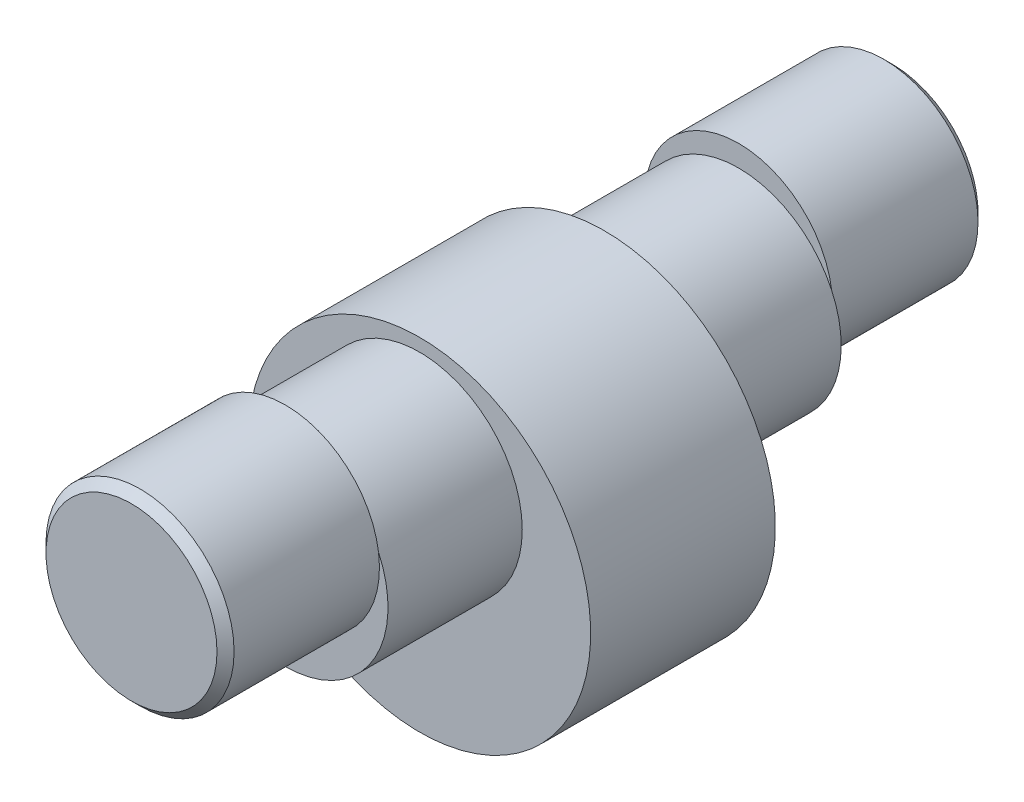
SolidWorks part; units mm, degrees
ref_plane "Plan de face" through (0, 0, 0) normal (0, 0, 1) x (1, 0, 0)
ref_plane "Plan de dessus" through (0, 0, 0) normal (0, 1, 0) x (1, 0, 0)
ref_plane "Plan de droite" through (0, 0, 0) normal (1, 0, 0) x (0, 0, -1)
sketch "Esquisse1" plane through (0, 0, 0) normal (0, 0, 1) x (1, 0, 0)
  circle A0 centre (0, 0) radius 20
  dimension "D1" = 40
extrude "Extrusion1" add sketch "Esquisse1" along normal mid plane 21.6
sketch "Esquisse2" plane through (0, 0, 10.8) normal (0, 0, 1) x (1, 0, 0)
  line L0 (0, 0) -> (0, 12.1345) construction
  circle A0 centre (0, 6.5) radius 12
  dimension "D2" = 24
  dimension "D1" = 6.5
extrude "Extrusion2" add sketch "Esquisse2" along normal blind 15.7
sketch "Esquisse3" plane through (0, 0, 26.5) normal (0, 0, 1) x (1, 0, 0)
  line L0 (0, 0) -> (0, 11.4659) construction
  circle A0 centre (0, 10) radius 11
  dimension "D2" = 22
  dimension "D1" = 10
extrude "Extrusion3" add sketch "Esquisse3" along normal blind 18
chamfer "Chanfrein1" distance 1 angle 45 1 edges at (11, 10, 44.5)
mirror "Symétrie2" about plane through (0, 0, 0) normal (0, 0, 1) of "Chanfrein1", "Extrusion3", "Extrusion2"
